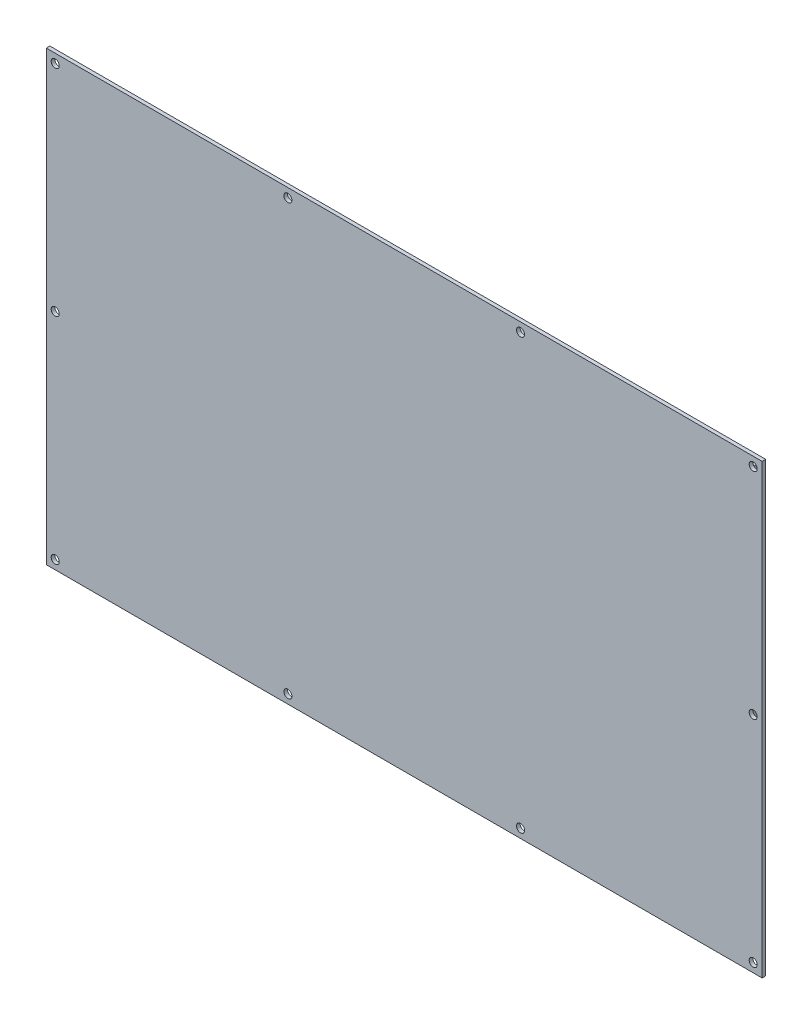
SolidWorks part; units mm, degrees
ref_plane "Ön Düzlem" through (0, 0, 0) normal (0, 0, 1) x (1, 0, 0)
ref_plane "Üst Düzlem" through (0, 0, 0) normal (0, 1, 0) x (1, 0, 0)
ref_plane "Sağ Düzlem" through (0, 0, 0) normal (1, 0, 0) x (0, 0, -1)
sketch "Çizim1" plane through (0, 0, 0) normal (0, 0, 1) x (1, 0, 0)
  line L1 (-200, -125) -> (200, -125)
  line L2 (-200, -125) -> (-200, 125)
  line L3 (-200, 125) -> (200, 125)
  line L4 (200, -125) -> (200, 125)
  line L5 (-200, -125) -> (200, 125) construction
  line L6 (-200, 125) -> (200, -125) construction
  point P0 (0, 0)
  dimension "D1" = 400
  dimension "D2" = 250
extrude "Yükseklik-Ekstrüzyon1" add sketch "Çizim1" along normal blind 2
sketch "Çizim3" plane through (0, 0, 2) normal (0, 0, 1) x (1, 0, 0)
  line L2 (0, 0) -> (109.1985, 0) construction
  circle A0 centre (-195, 120) radius 2.25
  circle A1 centre (-65, 120) radius 2.25
  circle A2 centre (65, 120) radius 2.25
  circle A3 centre (195, 120) radius 2.25
  circle A4 centre (-65, -120) radius 2.25
  circle A5 centre (65, -120) radius 2.25
  circle A6 centre (195, -120) radius 2.25
  circle A7 centre (-195, -120) radius 2.25
  circle A8 centre (-195, 0) radius 2.25
  circle A9 centre (195, 0) radius 2.25
  dimension "D1" = 2
  dimension "D3" = 4.5
  dimension "D2" = 120
  dimension "D6" = 120
  dimension "D4" = 4
  dimension "D5" = 2
extrude "Kes-Ekstrüzyon1" cut sketch "Çizim3" against normal up to next
sketch "Çizim4" plane through (0, 0, 0) normal (0, 0, -1) x (-1, 0, 0)
  line L1 (-190, -115) -> (190, -115)
  line L2 (-190, -115) -> (-190, 115)
  line L3 (-190, 115) -> (190, 115)
  line L4 (190, -115) -> (190, 115)
  line L5 (-190, -115) -> (190, 115) construction
  line L6 (-190, 115) -> (190, -115) construction
  point P0 (0, 0)
  dimension "D1" = 230
  dimension "D2" = 380
extrude "Yükseklik-Ekstrüzyon2" add sketch "Çizim4" along normal blind 6
